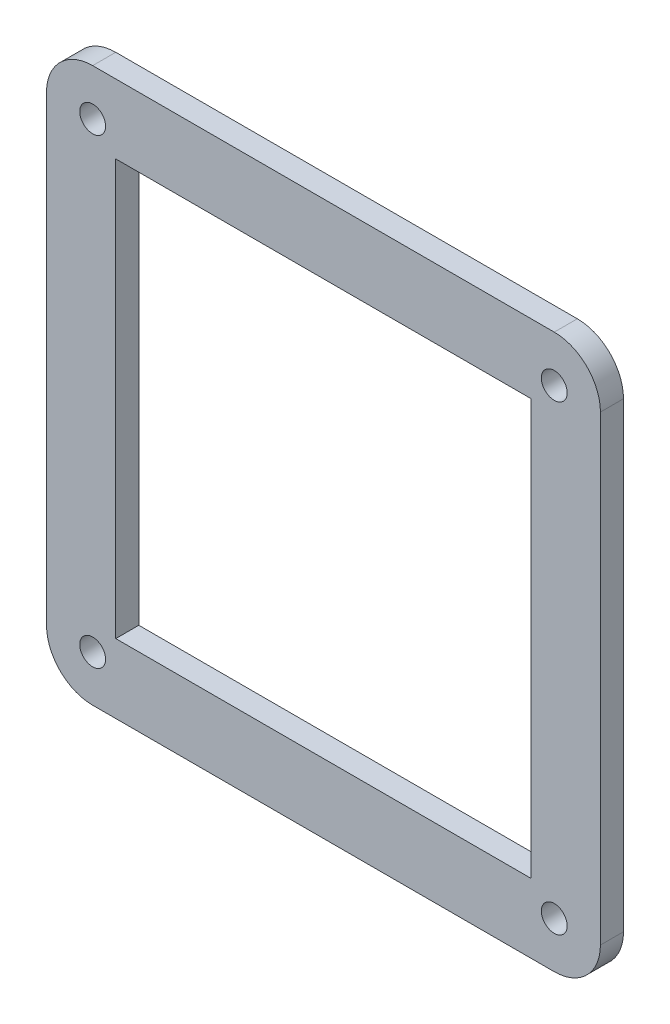
SolidWorks part; units mm, degrees
ref_plane "Alzado" through (0, 0, 0) normal (0, 0, 1) x (1, 0, 0)
ref_plane "Planta" through (0, 0, 0) normal (0, 1, 0) x (1, 0, 0)
ref_plane "Vista lateral" through (0, 0, 0) normal (1, 0, 0) x (0, 0, -1)
ref_plane "Plane1" through (0, 0, 0) normal (0, 0, -1) x (-1, 0, 0)
sketch "Sketch1" plane through (0, 0, 0) normal (0, 0, -1) x (-1, 0, 0)
  line L0 (-45, -45) -> (-45, 45)
  line L1 (-45, 45) -> (45, 45)
  line L2 (45, 45) -> (45, -45)
  line L3 (45, -45) -> (-45, -45)
  line L4 (60, -50) -> (60, 50)
  line L5 (50, 60) -> (-50, 60)
  line L6 (-60, 50) -> (-60, -50)
  line L7 (-50, -60) -> (50, -60)
  line L8 (0, 60) -> (0, -60) construction
  line L9 (-60, 0) -> (60, 0) construction
  line L10 (-50, 50) -> (50, -50) construction
  line L11 (-50, -50) -> (50, 50) construction
  circle A0 centre (50, -50) radius 2.8
  circle A1 centre (-50, -50) radius 2.8
  circle A2 centre (-50, 50) radius 2.8
  circle A3 centre (50, 50) radius 2.8
  arc A4 (60, 50) -> (50, 60) centre (50, 50) ccw
  arc A5 (-50, 60) -> (-60, 50) centre (-50, 50) ccw
  arc A6 (-60, -50) -> (-50, -60) centre (-50, -50) ccw
  arc A7 (50, -60) -> (60, -50) centre (50, -50) ccw
  dimension "D7" = 5.6
  dimension "D8" = 10
  dimension "D1" = 100
  dimension "D2" = 100
  dimension "D3" = 90
  dimension "D4" = 90
  dimension "D5" = 45
  dimension "D6" = 45
extrude "Boss-Extrude1" add sketch "Sketch1" against normal blind 5
